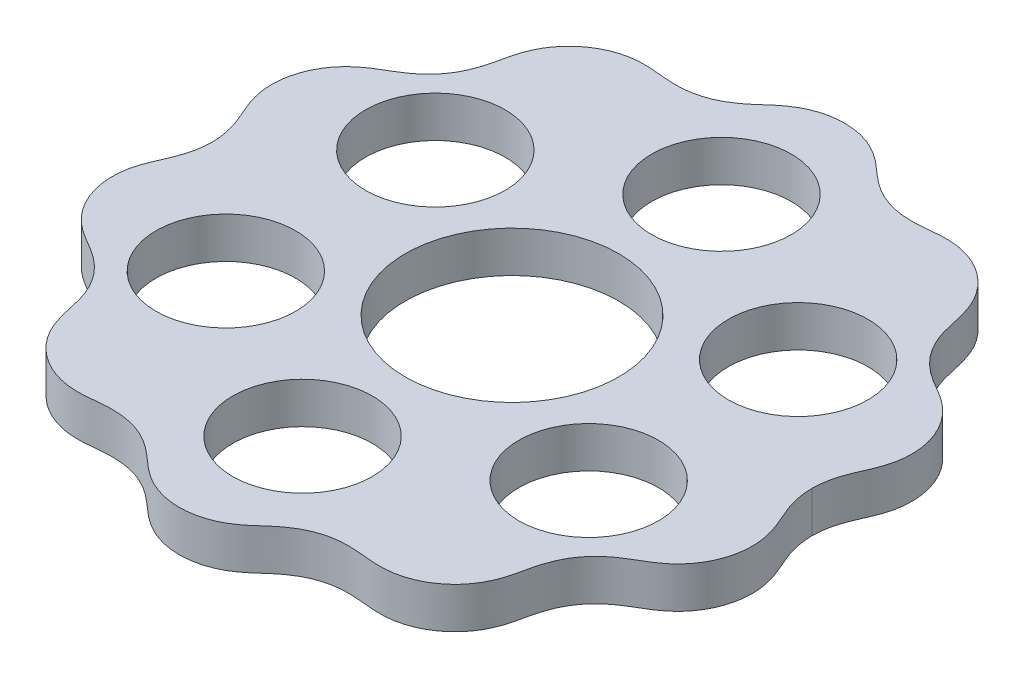
SolidWorks part; units mm, degrees
ref_plane "Front Plane" through (0, 0, 0) normal (0, 0, 1) x (1, 0, 0)
ref_plane "Top Plane" through (0, 0, 0) normal (0, 1, 0) x (1, 0, 0)
ref_plane "Right Plane" through (0, 0, 0) normal (1, 0, 0) x (0, 0, -1)
sketch "Sketch1" plane through (0, 0, 0) normal (0, 1, 0) x (1, 0, 0)
  circle A0 centre (0, 0) radius 13
  circle A1 centre (0, 0) radius 25.5 construction
  circle A2 centre (0, 25.5) radius 8.5
  circle A3 centre (22.0836, 12.75) radius 8.5
  circle A4 centre (22.0836, -12.75) radius 8.5
  circle A5 centre (0, -25.5) radius 8.5
  circle A6 centre (-22.0836, -12.75) radius 8.5
  circle A7 centre (-22.0836, 12.75) radius 8.5
  spline S0 degree 4 poles (38.858, 11.0852) (38.9322, 10.6047) (39.0099, 9.6527) (38.9421, 8.4984) (38.6357, 7.1878) (38.2864, 6.1974) (37.9882, 5.4798) (37.683, 4.7937) (37.3957, 4.1278) (37.1411, 3.4761) (36.9534, 2.9172) (36.8163, 2.4305) (36.7119, 1.9894) (36.6343, 1.5942) (36.5778, 1.2237) (36.5395, 0.8732) (36.5195, 0.614) (36.5099, 0.4402) (36.5043, 0.2856) (36.5014, 0.1595) (36.4995, 0.0195) (36.5002, -0.1092) (36.5052, -0.3492) (36.5165, -0.5716) (36.5378, -0.8544) (36.5744, -1.1968) (36.6281, -1.557) (36.7013, -1.9382) (36.7805, -2.282) (36.8613, -2.59) (36.9736, -2.9718) (37.1249, -3.4249) (37.3351, -3.9789) (37.6108, -4.6305) (37.913, -5.3088) (38.218, -6.0248) (38.5793, -7.0007) (38.9036, -8.2662) (39.0404, -9.8358) (38.8332, -11.6193) (38.3001, -13.2875) (37.487, -14.7883) (36.5194, -15.9854) (35.4632, -16.9217) (34.4806, -17.5844) (33.652, -18.0704) (32.7414, -18.5999) (31.7458, -19.2304) (30.6441, -20.104) (29.5519, -21.317) (28.7099, -22.6884) (28.1292, -24.1273) (27.764, -25.5368) (27.4986, -26.872) (27.1446, -28.2457) (26.5859, -29.6132) (25.7538, -30.9467) (24.6303, -32.1739) (23.3041, -33.1785) (21.8187, -33.928) (20.3544, -34.3562) (18.98, -34.5225) (17.8101, -34.5087) (16.8566, -34.4266) (15.9782, -34.3339) (15.1709, -34.2657) (14.1498, -34.2296) (12.9163, -34.2978) (11.4927, -34.5814) (10.0187, -35.1679) (8.7307, -35.9469) (7.6167, -36.8334) (6.6277, -37.7411) (5.5491, -38.6675) (4.2889, -39.4888) (2.8327, -40.1155) (1.2099, -40.4828) (-0.4524, -40.5514) (-2.1, -40.32) (-3.516, -39.8474) (-4.6848, -39.2366) (-5.5951, -38.6033) (-6.2913, -38.0314) (-6.9352, -37.4556) (-7.5529, -36.9053) (-8.3721, -36.2275) (-9.4173, -35.5016) (-10.7447, -34.8354) (-12.2749, -34.3962) (-13.5683, -34.2461) (-14.6093, -34.2407) (-15.4184, -34.2856) (-16.0966, -34.3467) (-16.984, -34.439) (-18.1297, -34.5342) (-19.5142, -34.4997) (-21.1001, -34.1777) (-22.6427, -33.5543) (-24.0472, -32.6623) (-25.2685, -31.5325) (-26.1543, -30.3477) (-26.7561, -29.2048) (-27.1372, -28.1922) (-27.3763, -27.3513) (-27.5642, -26.522) (-27.7363, -25.7129) (-27.9936, -24.6343) (-28.3991, -23.3794) (-29.0768, -22.0048) (-30.0541, -20.7188) (-31.0788, -19.746) (-32.0395, -19.0415) (-32.8641, -18.528) (-33.7908, -17.9899) (-34.8204, -17.3824) (-35.9613, -16.5376) (-37.0866, -15.3426) (-37.9865, -13.9433) (-38.6185, -12.4041) (-38.9637, -10.7767) (-39.0028, -9.321) (-38.8449, -8.0857) (-38.5926, -7.0813) (-38.3262, -6.297) (-38.0113, -5.5316) (-37.6749, -4.7759) (-37.3784, -4.0878) (-37.1368, -3.4613) (-36.9489, -2.8982) (-36.8252, -2.4645) (-36.7344, -2.0886) (-36.6616, -1.735) (-36.6042, -1.4037) (-36.5611, -1.0845) (-36.531, -0.7734) (-36.5136, -0.5202) (-36.5043, -0.3098) (-36.4995, -0.0654) (-36.4997, 0.0863) (-36.5054, 0.3578) (-36.5173, 0.5838) (-36.5395, 0.8738) (-36.5778, 1.2233) (-36.6343, 1.5944) (-36.7119, 1.9893) (-36.7969, 2.3486) (-36.8848, 2.6739) (-37.007, 3.0768) (-37.1717, 3.5546) (-37.3957, 4.1277) (-37.683, 4.7937) (-37.9882, 5.4798) (-38.2864, 6.1974) (-38.6357, 7.1878) (-38.9421, 8.4984) (-39.0099, 9.6527) (-38.9322, 10.6047) (-38.858, 11.0852) knots 0 0 0 0 0 0.01275 0.024998 0.030092 0.035186 0.04028 0.045374 0.049791 0.054208 0.058625 0.060834 0.063042 0.066105 0.069167 0.070698 0.07223 0.072995 0.073761 0.074526 0.075292 0.07679 0.078287 0.079785 0.081283 0.084278 0.087273 0.089361 0.091448 0.093536 0.095623 0.099798 0.103973 0.109075 0.114177 0.119279 0.124381 0.136358 0.148337 0.160314 0.171165 0.182016 0.192867 0.200455 0.208044 0.213054 0.218064 0.228085 0.238937 0.249793 0.260646 0.270064 0.279482 0.287924 0.296367 0.307217 0.318067 0.328918 0.339769 0.350619 0.36147 0.368707 0.375944 0.381255 0.386566 0.391878 0.397189 0.408044 0.418897 0.42975 0.438567 0.447383 0.456177 0.464971 0.475821 0.486672 0.497522 0.508373 0.519224 0.530074 0.536458 0.542842 0.548267 0.553691 0.559116 0.564541 0.576146 0.587 0.597853 0.606066 0.610172 0.614279 0.619103 0.623927 0.633575 0.644425 0.655276 0.666126 0.676977 0.687828 0.698679 0.70471 0.710741 0.716165 0.721589 0.727013 0.732437 0.74525 0.756105 0.766961 0.77457 0.782178 0.787304 0.792429 0.80268 0.813531 0.824381 0.835231 0.846082 0.856933 0.867783 0.873212 0.878641 0.884065 0.889489 0.894913 0.900338 0.903717 0.907097 0.910477 0.912166 0.913856 0.916569 0.919282 0.920639 0.921995 0.923352 0.924708 0.926239 0.92777 0.929302 0.930833 0.933895 0.936958 0.939166 0.941375 0.943584 0.945792 0.950209 0.954626 0.95972 0.964814 0.969908 0.975002 0.98725 1 1 1 1 1 construction
  spline S1 degree 4 poles (36.5, 0) (36.5, -0.0485) (36.5009, -0.1441) (36.5052, -0.3492) (36.5165, -0.5716) (36.5378, -0.8544) (36.5744, -1.1968) (36.6281, -1.557) (36.7013, -1.9382) (36.7805, -2.282) (36.8613, -2.59) (36.9736, -2.9718) (37.1249, -3.4249) (37.3351, -3.9789) (37.6108, -4.6305) (37.913, -5.3088) (38.218, -6.0248) (38.5793, -7.0007) (38.9036, -8.2662) (39.0404, -9.8358) (38.8332, -11.6193) (38.3001, -13.2875) (37.487, -14.7883) (36.5194, -15.9854) (35.4632, -16.9217) (34.4806, -17.5844) (33.652, -18.0704) (32.7414, -18.5999) (31.7458, -19.2304) (30.6441, -20.104) (29.5519, -21.317) (28.7099, -22.6884) (28.1292, -24.1273) (27.764, -25.5368) (27.4986, -26.872) (27.1446, -28.2457) (26.5859, -29.6132) (25.7538, -30.9467) (24.6303, -32.1739) (23.3041, -33.1785) (21.8187, -33.928) (20.3544, -34.3562) (18.98, -34.5225) (17.8101, -34.5087) (16.8566, -34.4266) (15.9782, -34.3339) (15.1709, -34.2657) (14.1498, -34.2296) (12.9163, -34.2978) (11.4927, -34.5814) (10.0187, -35.1679) (8.7307, -35.9469) (7.6167, -36.8334) (6.6277, -37.7411) (5.5491, -38.6675) (4.2889, -39.4888) (2.8327, -40.1155) (1.2099, -40.4828) (-0.4524, -40.5514) (-2.1, -40.32) (-3.516, -39.8474) (-4.6848, -39.2366) (-5.5951, -38.6033) (-6.2913, -38.0314) (-6.9352, -37.4556) (-7.5529, -36.9053) (-8.3721, -36.2275) (-9.4173, -35.5016) (-10.7447, -34.8354) (-12.2749, -34.3962) (-13.5683, -34.2461) (-14.6093, -34.2407) (-15.4184, -34.2856) (-16.0966, -34.3467) (-16.984, -34.439) (-18.1297, -34.5342) (-19.5142, -34.4997) (-21.1001, -34.1777) (-22.6427, -33.5543) (-24.0472, -32.6623) (-25.2685, -31.5325) (-26.1543, -30.3477) (-26.7561, -29.2048) (-27.1372, -28.1922) (-27.3763, -27.3513) (-27.5642, -26.522) (-27.7363, -25.7129) (-27.9936, -24.6343) (-28.3991, -23.3794) (-29.0768, -22.0048) (-30.0541, -20.7188) (-31.0788, -19.746) (-32.0395, -19.0415) (-32.8641, -18.528) (-33.7908, -17.9899) (-34.8204, -17.3824) (-35.9613, -16.5376) (-37.0866, -15.3426) (-37.9865, -13.9433) (-38.6185, -12.4041) (-38.9637, -10.7767) (-39.0028, -9.321) (-38.8449, -8.0857) (-38.5926, -7.0813) (-38.3262, -6.297) (-38.0113, -5.5316) (-37.6749, -4.7759) (-37.3784, -4.0878) (-37.1368, -3.4613) (-36.9489, -2.8982) (-36.8252, -2.4645) (-36.7344, -2.0886) (-36.6616, -1.735) (-36.6042, -1.4037) (-36.5611, -1.0845) (-36.531, -0.7734) (-36.5136, -0.5202) (-36.5043, -0.3098) (-36.5008, -0.1322) (-36.5, -0.0439) (-36.5, 0) knots 0.075292 0.075292 0.075292 0.075292 0.075292 0.07679 0.078287 0.079785 0.081283 0.084278 0.087273 0.089361 0.091448 0.093536 0.095623 0.099798 0.103973 0.109075 0.114177 0.119279 0.124381 0.136358 0.148337 0.160314 0.171165 0.182016 0.192867 0.200455 0.208044 0.213054 0.218064 0.228085 0.238937 0.249793 0.260646 0.270064 0.279482 0.287924 0.296367 0.307217 0.318067 0.328918 0.339769 0.350619 0.36147 0.368707 0.375944 0.381255 0.386566 0.391878 0.397189 0.408044 0.418897 0.42975 0.438567 0.447383 0.456177 0.464971 0.475821 0.486672 0.497522 0.508373 0.519224 0.530074 0.536458 0.542842 0.548267 0.553691 0.559116 0.564541 0.576146 0.587 0.597853 0.606066 0.610172 0.614279 0.619103 0.623927 0.633575 0.644425 0.655276 0.666126 0.676977 0.687828 0.698679 0.70471 0.710741 0.716165 0.721589 0.727013 0.732437 0.74525 0.756105 0.766961 0.77457 0.782178 0.787304 0.792429 0.80268 0.813531 0.824381 0.835231 0.846082 0.856933 0.867783 0.873212 0.878641 0.884065 0.889489 0.894913 0.900338 0.903717 0.907097 0.910477 0.912166 0.913856 0.916569 0.919282 0.920639 0.921995 0.923352 0.924708 0.924708 0.924708 0.924708 0.924708
  spline S2 degree 4 poles (-38.858, -11.0852) (-38.9322, -10.6047) (-39.0099, -9.6527) (-38.9421, -8.4984) (-38.6357, -7.1878) (-38.2864, -6.1974) (-37.9882, -5.4798) (-37.683, -4.7937) (-37.3957, -4.1277) (-37.1717, -3.5546) (-37.007, -3.0768) (-36.8848, -2.6739) (-36.7969, -2.3487) (-36.7119, -1.9892) (-36.6456, -1.652) (-36.5953, -1.3382) (-36.5586, -1.0489) (-36.535, -0.8153) (-36.5195, -0.614) (-36.5099, -0.4403) (-36.5043, -0.2858) (-36.5014, -0.1597) (-36.4995, -0.0193) (-36.5001, 0.0875) (-36.5031, 0.2488) (-36.5095, 0.4308) (-36.5187, 0.6009) (-36.5378, 0.8538) (-36.5744, 1.1972) (-36.6281, 1.5568) (-36.7013, 1.9383) (-36.7983, 2.3595) (-36.9244, 2.8204) (-37.0966, 3.3504) (-37.3351, 3.9789) (-37.6108, 4.6304) (-37.913, 5.3088) (-38.218, 6.0248) (-38.5793, 7.0007) (-38.9036, 8.2662) (-39.0404, 9.8358) (-38.8332, 11.6193) (-38.3001, 13.2875) (-37.487, 14.7883) (-36.5194, 15.9854) (-35.4632, 16.9217) (-34.4806, 17.5844) (-33.652, 18.0704) (-32.9065, 18.5039) (-32.257, 18.9066) (-31.4454, 19.4687) (-30.5156, 20.2467) (-29.5519, 21.317) (-28.7099, 22.6884) (-28.1292, 24.1273) (-27.764, 25.5368) (-27.4986, 26.872) (-27.1446, 28.2457) (-26.5859, 29.6132) (-25.7538, 30.9467) (-24.6303, 32.1739) (-23.3041, 33.1785) (-21.8187, 33.928) (-20.3544, 34.3562) (-18.98, 34.5225) (-17.8101, 34.5087) (-16.8566, 34.4266) (-15.9782, 34.3339) (-15.1709, 34.2657) (-14.1498, 34.2296) (-12.9163, 34.2978) (-11.4927, 34.5814) (-10.0187, 35.1679) (-8.7307, 35.9469) (-7.6167, 36.8334) (-6.6277, 37.7411) (-5.5491, 38.6675) (-4.2889, 39.4888) (-2.8327, 40.1155) (-1.2099, 40.4828) (0.4524, 40.5514) (2.1, 40.32) (3.516, 39.8474) (4.6848, 39.2366) (5.5951, 38.6033) (6.2913, 38.0314) (6.9352, 37.4556) (7.5529, 36.9053) (8.3721, 36.2275) (9.4173, 35.5016) (10.7447, 34.8354) (12.2749, 34.3962) (13.5683, 34.2461) (14.6093, 34.2407) (15.4184, 34.2856) (16.0966, 34.3467) (16.984, 34.439) (18.1297, 34.5342) (19.5142, 34.4997) (21.1001, 34.1777) (22.6427, 33.5543) (24.0472, 32.6623) (25.2685, 31.5325) (26.1543, 30.3477) (26.7561, 29.2048) (27.1372, 28.1922) (27.3763, 27.3513) (27.5642, 26.522) (27.7363, 25.7129) (27.9936, 24.6343) (28.3991, 23.3794) (29.0768, 22.0048) (30.0541, 20.7188) (31.0788, 19.746) (32.0395, 19.0415) (32.8641, 18.528) (33.7908, 17.9899) (34.8204, 17.3824) (35.9613, 16.5376) (37.0866, 15.3426) (37.9865, 13.9433) (38.6185, 12.4041) (38.9637, 10.7767) (39.0028, 9.321) (38.8449, 8.0857) (38.5926, 7.0813) (38.3262, 6.297) (38.0113, 5.5316) (37.6749, 4.7759) (37.3784, 4.0878) (37.1368, 3.4612) (36.9693, 2.9594) (36.8606, 2.5884) (36.7798, 2.2765) (36.7214, 2.0254) (36.6616, 1.735) (36.6042, 1.4036) (36.5611, 1.0847) (36.531, 0.7731) (36.5153, 0.5458) (36.5078, 0.3885) (36.5025, 0.222) (36.5, 0.0774) (36.4996, -0.0243) (36.5014, -0.1598) (36.5043, -0.2859) (36.5099, -0.4403) (36.5195, -0.614) (36.535, -0.8153) (36.5586, -1.0489) (36.5953, -1.3382) (36.6455, -1.652) (36.7119, -1.9892) (36.8163, -2.4307) (36.9534, -2.9171) (37.1411, -3.4761) (37.3957, -4.1277) (37.683, -4.7937) (37.9882, -5.4798) (38.2864, -6.1974) (38.6357, -7.1878) (38.9421, -8.4984) (39.0099, -9.6527) (38.9322, -10.6047) (38.858, -11.0852) knots 0 0 0 0 0 0.01275 0.024998 0.030092 0.035186 0.04028 0.045374 0.049791 0.054208 0.056416 0.058625 0.060834 0.063042 0.066105 0.067636 0.069167 0.070698 0.07223 0.072995 0.073761 0.074526 0.075292 0.07679 0.077538 0.078287 0.079785 0.081283 0.084278 0.087273 0.089361 0.091448 0.095623 0.099798 0.103973 0.109075 0.114177 0.119279 0.124381 0.136358 0.148337 0.160314 0.171165 0.182016 0.192867 0.200455 0.208044 0.213054 0.218064 0.223074 0.228085 0.238937 0.249793 0.260646 0.270064 0.279482 0.287924 0.296367 0.307217 0.318067 0.328918 0.339769 0.350619 0.36147 0.368707 0.375944 0.381255 0.386566 0.391878 0.397189 0.408044 0.418897 0.42975 0.438567 0.447383 0.456177 0.464971 0.475821 0.486672 0.497522 0.508373 0.519224 0.530074 0.536458 0.542842 0.548267 0.553691 0.559116 0.564541 0.576146 0.587 0.597853 0.606066 0.610172 0.614279 0.619103 0.623927 0.633575 0.644425 0.655276 0.666126 0.676977 0.687828 0.698679 0.70471 0.710741 0.716165 0.721589 0.727013 0.732437 0.74525 0.756105 0.766961 0.77457 0.782178 0.787304 0.792429 0.80268 0.813531 0.824381 0.835231 0.846082 0.856933 0.867783 0.873212 0.878641 0.884065 0.889489 0.894913 0.900338 0.903717 0.907097 0.908787 0.910477 0.912166 0.913856 0.916569 0.919282 0.920639 0.921995 0.922673 0.923352 0.924708 0.925474 0.926239 0.927005 0.92777 0.929302 0.930833 0.932364 0.933895 0.936958 0.939166 0.941375 0.945792 0.950209 0.954626 0.95972 0.964814 0.969908 0.975002 0.98725 1 1 1 1 1 construction
  spline S3 degree 4 poles (-36.5, 0) (-36.5, 0.0485) (-36.5007, 0.1203) (-36.5031, 0.2488) (-36.5095, 0.4308) (-36.5187, 0.6009) (-36.5378, 0.8538) (-36.5744, 1.1972) (-36.6281, 1.5568) (-36.7013, 1.9383) (-36.7983, 2.3595) (-36.9244, 2.8204) (-37.0966, 3.3504) (-37.3351, 3.9789) (-37.6108, 4.6304) (-37.913, 5.3088) (-38.218, 6.0248) (-38.5793, 7.0007) (-38.9036, 8.2662) (-39.0404, 9.8358) (-38.8332, 11.6193) (-38.3001, 13.2875) (-37.487, 14.7883) (-36.5194, 15.9854) (-35.4632, 16.9217) (-34.4806, 17.5844) (-33.652, 18.0704) (-32.9065, 18.5039) (-32.257, 18.9066) (-31.4454, 19.4687) (-30.5156, 20.2467) (-29.5519, 21.317) (-28.7099, 22.6884) (-28.1292, 24.1273) (-27.764, 25.5368) (-27.4986, 26.872) (-27.1446, 28.2457) (-26.5859, 29.6132) (-25.7538, 30.9467) (-24.6303, 32.1739) (-23.3041, 33.1785) (-21.8187, 33.928) (-20.3544, 34.3562) (-18.98, 34.5225) (-17.8101, 34.5087) (-16.8566, 34.4266) (-15.9782, 34.3339) (-15.1709, 34.2657) (-14.1498, 34.2296) (-12.9163, 34.2978) (-11.4927, 34.5814) (-10.0187, 35.1679) (-8.7307, 35.9469) (-7.6167, 36.8334) (-6.6277, 37.7411) (-5.5491, 38.6675) (-4.2889, 39.4888) (-2.8327, 40.1155) (-1.2099, 40.4828) (0.4524, 40.5514) (2.1, 40.32) (3.516, 39.8474) (4.6848, 39.2366) (5.5951, 38.6033) (6.2913, 38.0314) (6.9352, 37.4556) (7.5529, 36.9053) (8.3721, 36.2275) (9.4173, 35.5016) (10.7447, 34.8354) (12.2749, 34.3962) (13.5683, 34.2461) (14.6093, 34.2407) (15.4184, 34.2856) (16.0966, 34.3467) (16.984, 34.439) (18.1297, 34.5342) (19.5142, 34.4997) (21.1001, 34.1777) (22.6427, 33.5543) (24.0472, 32.6623) (25.2685, 31.5325) (26.1543, 30.3477) (26.7561, 29.2048) (27.1372, 28.1922) (27.3763, 27.3513) (27.5642, 26.522) (27.7363, 25.7129) (27.9936, 24.6343) (28.3991, 23.3794) (29.0768, 22.0048) (30.0541, 20.7188) (31.0788, 19.746) (32.0395, 19.0415) (32.8641, 18.528) (33.7908, 17.9899) (34.8204, 17.3824) (35.9613, 16.5376) (37.0866, 15.3426) (37.9865, 13.9433) (38.6185, 12.4041) (38.9637, 10.7767) (39.0028, 9.321) (38.8449, 8.0857) (38.5926, 7.0813) (38.3262, 6.297) (38.0113, 5.5316) (37.6749, 4.7759) (37.3784, 4.0878) (37.1368, 3.4612) (36.9693, 2.9594) (36.8606, 2.5884) (36.7798, 2.2765) (36.7214, 2.0254) (36.6616, 1.735) (36.6042, 1.4036) (36.5611, 1.0847) (36.531, 0.7731) (36.5153, 0.5458) (36.5078, 0.3885) (36.5025, 0.222) (36.5006, 0.1092) (36.5, 0.0439) (36.5, 0) knots 0.075292 0.075292 0.075292 0.075292 0.075292 0.07679 0.077538 0.078287 0.079785 0.081283 0.084278 0.087273 0.089361 0.091448 0.095623 0.099798 0.103973 0.109075 0.114177 0.119279 0.124381 0.136358 0.148337 0.160314 0.171165 0.182016 0.192867 0.200455 0.208044 0.213054 0.218064 0.223074 0.228085 0.238937 0.249793 0.260646 0.270064 0.279482 0.287924 0.296367 0.307217 0.318067 0.328918 0.339769 0.350619 0.36147 0.368707 0.375944 0.381255 0.386566 0.391878 0.397189 0.408044 0.418897 0.42975 0.438567 0.447383 0.456177 0.464971 0.475821 0.486672 0.497522 0.508373 0.519224 0.530074 0.536458 0.542842 0.548267 0.553691 0.559116 0.564541 0.576146 0.587 0.597853 0.606066 0.610172 0.614279 0.619103 0.623927 0.633575 0.644425 0.655276 0.666126 0.676977 0.687828 0.698679 0.70471 0.710741 0.716165 0.721589 0.727013 0.732437 0.74525 0.756105 0.766961 0.77457 0.782178 0.787304 0.792429 0.80268 0.813531 0.824381 0.835231 0.846082 0.856933 0.867783 0.873212 0.878641 0.884065 0.889489 0.894913 0.900338 0.903717 0.907097 0.908787 0.910477 0.912166 0.913856 0.916569 0.919282 0.920639 0.921995 0.922673 0.923352 0.924708 0.924708 0.924708 0.924708 0.924708
  point P24 (0, 0)
  dimension "D1" = 26
  dimension "D2" = 17
  dimension "D4" = 51
  dimension "D3" = 6
extrude "Boss-Extrude1" add sketch "Sketch1" along normal blind 5
